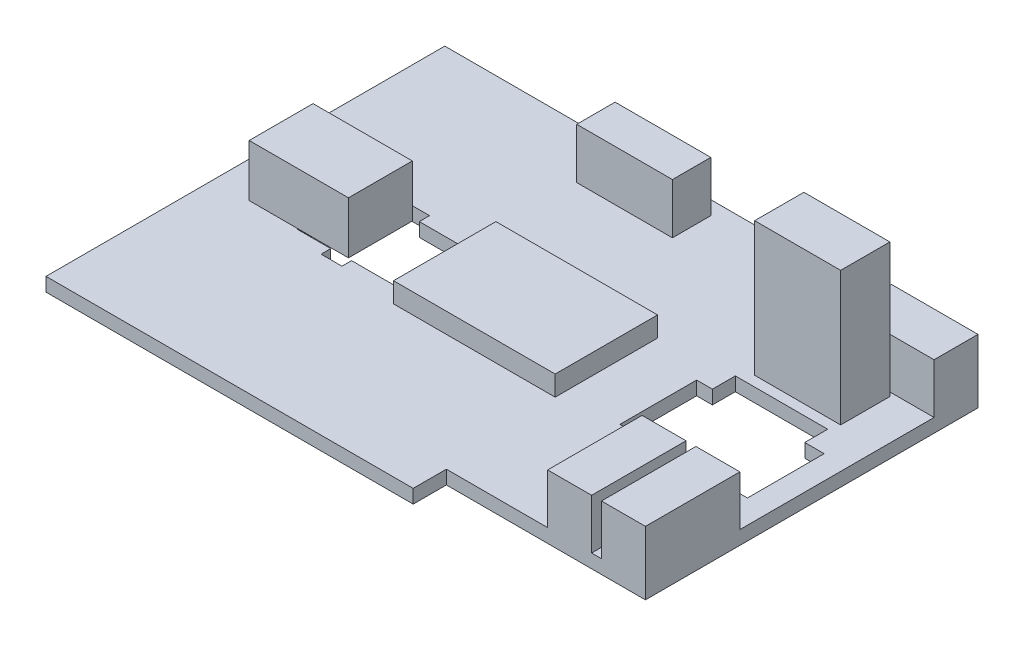
SolidWorks part; units mm, degrees
material "ABS"
ref_plane "Front Plane" through (0, 0, 0) normal (0, 0, 1) x (1, 0, 0)
ref_plane "Top Plane" through (0, 0, 0) normal (0, 1, 0) x (1, 0, 0)
ref_plane "Right Plane" through (0, 0, 0) normal (1, 0, 0) x (0, 0, -1)
sketch "Sketch1" plane through (0, 0, 0) normal (0, 1, 0) x (1, 0, 0)
  line L0 (46.12, 45.94) -> (71.12, 45.94)
  line L1 (0, 0) -> (46.12, 0)
  line L2 (0, 0) -> (0, 50.09)
  line L3 (0, 50.09) -> (46.12, 50.09)
  line L4 (46.12, 0) -> (46.12, 4.17)
  line L5 (71.12, 45.94) -> (71.12, 4.17)
  line L6 (71.12, 4.17) -> (46.12, 4.17)
  line L7 (46.12, 45.94) -> (46.12, 50.09)
  dimension "D1" = 46.12
  dimension "D2" = 50.09
  dimension "D3" = 41.77
  dimension "D4" = 4.17
  dimension "D5" = 25
extrude "Boss-Extrude1" add sketch "Sketch1" against normal blind 1.72
sketch "Sketch2" plane through (0, 0, 0) normal (0, 1, 0) x (1, 0, 0)
  line L0 (71.12, 45.94) -> (46.12, 45.94) construction
  line L1 (65.72, 32.46) -> (54.12, 32.46)
  line L2 (65.72, 32.46) -> (65.72, 29.58)
  line L3 (65.72, 17.62) -> (54.12, 17.62)
  line L4 (54.12, 32.46) -> (54.12, 29.58)
  line L5 (65.72, 29.58) -> (68.16, 29.58)
  line L6 (52.14, 29.58) -> (54.12, 29.58)
  line L7 (52.14, 29.58) -> (52.14, 19.94)
  line L8 (52.14, 19.94) -> (54.12, 19.94)
  line L9 (68.16, 29.58) -> (68.16, 19.94)
  line L10 (65.72, 19.94) -> (68.16, 19.94)
  line L11 (65.72, 19.94) -> (65.72, 17.62)
  line L12 (54.12, 19.94) -> (54.12, 17.62)
  line L13 (71.12, 4.17) -> (71.12, 45.94) construction
  line L14 (17.483, 20.9) -> (17.483, 19.69)
  line L15 (44.54, 29.4) -> (17.483, 29.4)
  line L16 (44.54, 29.4) -> (44.54, 20.9)
  line L17 (44.54, 20.9) -> (17.483, 20.9)
  line L18 (10.663, 29.4) -> (10.663, 20.9)
  line L19 (14.863, 30.69) -> (17.483, 30.69)
  line L20 (14.863, 30.69) -> (14.863, 29.4)
  line L21 (14.863, 19.69) -> (17.483, 19.69)
  line L22 (17.483, 30.69) -> (17.483, 29.4)
  line L23 (14.863, 20.9) -> (14.863, 19.69)
  line L24 (14.863, 29.4) -> (10.663, 29.4)
  line L25 (14.863, 20.9) -> (10.663, 20.9)
  line L26 (46.12, 50.09) -> (0, 50.09) construction
  line L27 (0, 50.09) -> (0, 0) construction
  dimension "D1" = 13.48
  dimension "D2" = 16.36
  dimension "D3" = 2.32
  dimension "D4" = 14.84
  dimension "D5" = 5.4
  dimension "D6" = 2.96
  dimension "D7" = 11.6
  dimension "D8" = 16.02
  dimension "D9" = 8.5
  dimension "D10" = 11
  dimension "D11" = 19.4
  dimension "D12" = 20.69
  dimension "D13" = 10.663
  dimension "D14" = 2.62
  dimension "D15" = 4.2
  dimension "D16" = 7.6
extrude "Cut-Extrude1" cut sketch "Sketch2" against normal up to surface (1.72 mm away) up to face at (40.84, -1.72, -25.05)
sketch "Sketch6" plane through (0, 0, 0) normal (0, 1, 0) x (1, 0, 0)
  line L0 (46.12, 4.17) -> (71.12, 4.17) construction
  line L1 (71.12, 4.17) -> (65.6, 4.17)
  line L2 (71.12, 4.17) -> (71.12, 16.03)
  line L3 (71.12, 16.03) -> (65.6, 16.03)
  line L4 (65.6, 4.17) -> (65.6, 16.03)
  line L5 (64.36, 4.17) -> (58.84, 4.17)
  line L6 (64.36, 4.17) -> (64.36, 16.03)
  line L7 (64.36, 16.03) -> (58.84, 16.03)
  line L8 (58.84, 4.17) -> (58.84, 16.03)
  line L10 (71.12, 45.94) -> (60.27, 45.94)
  line L11 (71.12, 45.94) -> (71.12, 40.42)
  line L12 (71.12, 40.42) -> (60.27, 40.42)
  line L13 (60.27, 45.94) -> (60.27, 40.42)
  dimension "D1" = 5.52
  dimension "D2" = 10.85
  dimension "D3" = 5.52
  dimension "D4" = 11.86
  dimension "D5" = 1.24
extrude "switches" add sketch "Sketch6" along normal blind 6.28 contours L11 L10 L13 L12 | L2 L1 L4 L3 | L6 L5 L8 L7
sketch "Sketch7" plane through (0, 0, 0) normal (0, 1, 0) x (1, 0, 0)
  line L0 (71.12, 16.03) -> (71.12, 40.42) construction
  line L1 (66.07, 39.92) -> (55.27, 39.92)
  line L2 (66.07, 39.92) -> (66.07, 33.74)
  line L3 (66.07, 33.74) -> (55.27, 33.74)
  line L4 (55.27, 39.92) -> (55.27, 33.74)
  line L5 (60.27, 45.94) -> (46.12, 45.94) construction
  dimension "D1" = 6.18
  dimension "D2" = 10.8
  dimension "D3" = 5.05
  dimension "D4" = 6.02
extrude "scrollWheel" add sketch "Sketch7" along normal blind 16.82
sketch "Sketch8" plane through (0, 0, 0) normal (0, 1, 0) x (1, 0, 0)
  line L0 (52.14, 29.58) -> (52.14, 19.94) construction
  line L1 (24.82, 31.69) -> (45.12, 31.69)
  line L2 (24.82, 31.69) -> (24.82, 18.83)
  line L3 (24.82, 18.83) -> (45.12, 18.83)
  line L4 (45.12, 31.69) -> (45.12, 18.83)
  line L5 (46.12, 50.09) -> (0, 50.09) construction
  dimension "D1" = 7.02
  dimension "D2" = 12.86
  dimension "D3" = 18.4
  dimension "D4" = 20.3
extrude "chip" add sketch "Sketch8" along normal blind 2.52
sketch "Sketch9" plane through (0, 0, 0) normal (0, 1, 0) x (1, 0, 0)
  line L0 (46.12, 50.09) -> (0, 50.09) construction
  line L1 (23.13, 48.35) -> (35.15, 48.35)
  line L2 (23.13, 48.35) -> (23.13, 43.53)
  line L3 (23.13, 43.53) -> (35.15, 43.53)
  line L4 (35.15, 48.35) -> (35.15, 43.53)
  line L5 (46.12, 45.94) -> (46.12, 50.09) construction
  dimension "D1" = 12.02
  dimension "D2" = 4.82
  dimension "D3" = 1.74
  dimension "D4" = 10.97
extrude "USB Connection" add sketch "Sketch9" along normal blind 6.34
sketch "Sketch10" plane through (0, 0, 0) normal (0, 1, 0) x (1, 0, 0)
  line L0 (0, 50.09) -> (0, 0) construction
  line L1 (4.52, 29.02) -> (16.99, 29.02)
  line L2 (4.52, 29.02) -> (4.52, 21)
  line L3 (4.52, 21) -> (16.99, 21)
  line L4 (16.99, 29.02) -> (16.99, 21)
  line L6 (0, 0) -> (46.12, 0) construction
  dimension "D1" = 12.47
  dimension "D2" = 4.52
  dimension "D3" = 8.02
  dimension "D4" = 21
extrude "laser" add sketch "Sketch10" along normal blind 6.54
